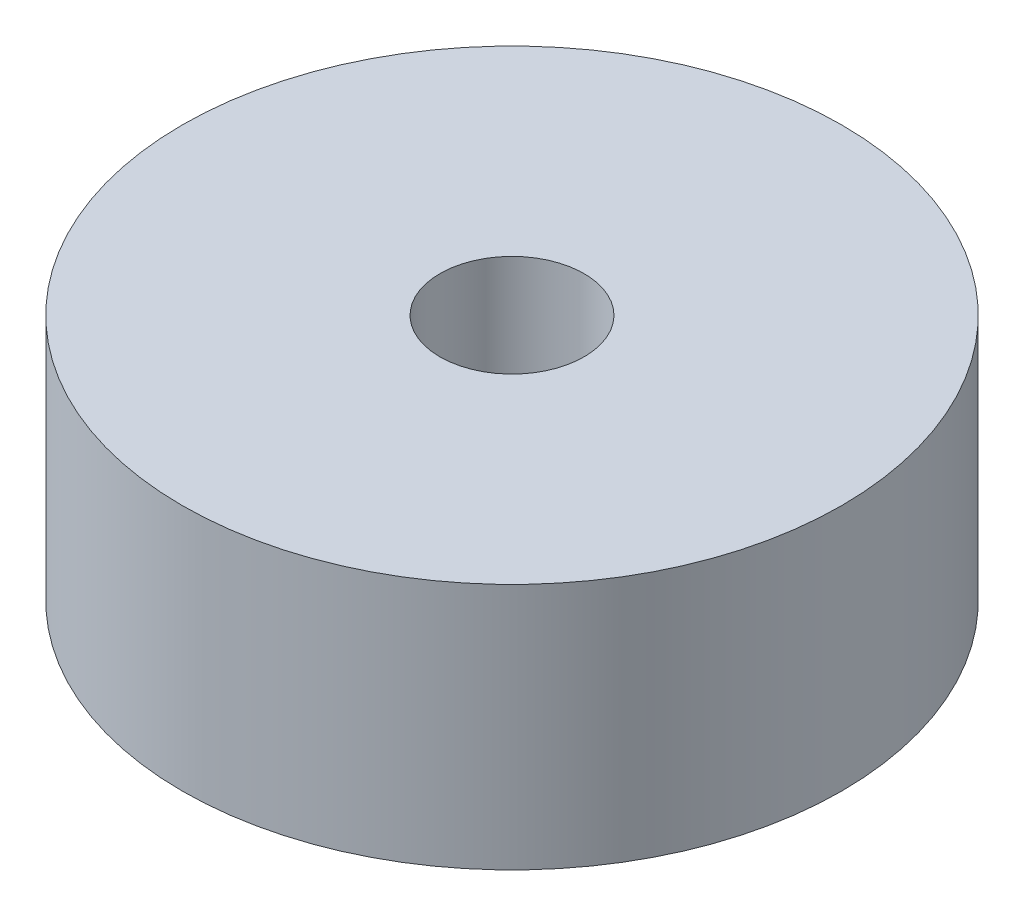
SolidWorks part; units mm, degrees
ref_plane "Front Plane" through (0, 0, 0) normal (0, 0, 1) x (1, 0, 0)
ref_plane "Top Plane" through (0, 0, 0) normal (0, 1, 0) x (1, 0, 0)
ref_plane "Right Plane" through (0, 0, 0) normal (1, 0, 0) x (0, 0, -1)
sketch "Sketch1" plane through (0, 0, 0) normal (0, 1, 0) x (1, 0, 0)
  circle A0 centre (0, 0) radius 4
  dimension "D1" = 8
extrude "Boss-Extrude1" add sketch "Sketch1" along normal blind 3 contours A0
sketch "Sketch2" plane through (0, 3, 0) normal (0, 1, 0) x (1, 0, 0)
  circle A0 centre (0, 0) radius 0.875
  dimension "D1" = 1.75
extrude "Cut-Extrude1" cut sketch "Sketch2" against normal through all
